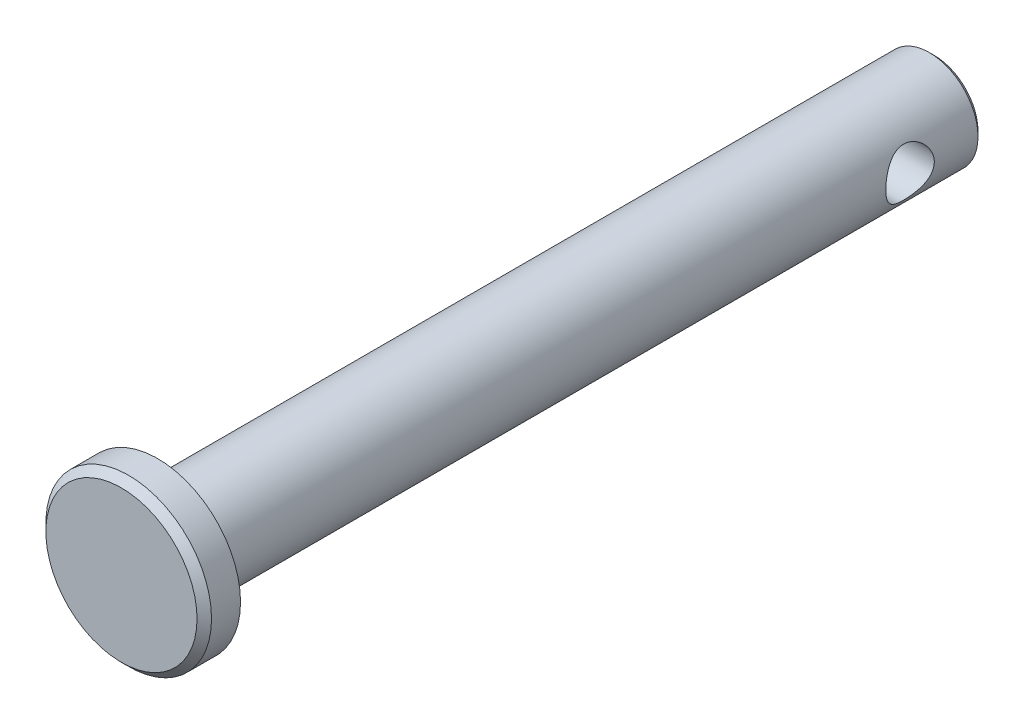
SolidWorks part; units mm, degrees
ref_plane "Front" through (0, 0, 0) normal (0, 0, 1) x (1, 0, 0)
ref_plane "Top" through (0, 0, 0) normal (0, 1, 0) x (1, 0, 0)
ref_plane "Right" through (0, 0, 0) normal (1, 0, 0) x (0, 0, -1)
sketch "Sketch1" plane through (0, 0, 0) normal (0, 0, 1) x (1, 0, 0)
  circle A0 centre (0, 0) radius 2.3812
  point P3 (0, 2.3812)
  point P4 (0, -2.3812)
  dimension "dia" = 4.7625
extrude "Extrude1" add sketch "Sketch1" along normal mid plane 38.1
sketch "Sketch2" plane through (0, 0, 19.05) normal (0, 0, 1) x (1, 0, 0)
  circle A0 centre (0, 0) radius 4.064
  dimension "head dia" = 8.128
extrude "Extrude2" add sketch "Sketch2" along normal blind 1.778
chamfer "Chamfer1" distance 0.3556 angle 45 1 edges at (4.064, 0, 20.828)
sketch "Sketch3" plane through (0, 0, 0) normal (1, 0, 0) x (0, 0, -1)
  line L0 (-19.05, -2.3812) -> (-19.05, 2.3812) construction
  circle A0 centre (15.4781, 0) radius 1.1906
  point P2 (14.2875, 0)
  dimension "hole dia" = 2.3813
  dimension "useable Lg" = 33.3375
extrude "Extrude3" cut sketch "Sketch3" against normal through all and the other way through all
chamfer "Chamfer2" distance 0.2381 angle 45 1 edges at (2.3812, 0, -19.05)
ref_plane "Plane1" through (0, 0, -15.4781) normal (0, 0, 1) x (1, 0, 0)
sketch "Sketch8" plane through (0, 0, 0) normal (1, 0, 0) x (0, 0, -1)
  line L0 (-20.828, 3.7084) -> (-20.828, -3.7084) construction
  line L1 (-20.4724, -4.064) -> (-19.05, -4.064) construction
  line L2 (19.05, -2.1431) -> (19.05, 2.1431) construction
  point P0 (-20.828, 4.064)
  point P1 (-19.05, 4.064)
  point P5 (19.05, 2.3812)
  point P8 (-20.828, -4.064)
  point P9 (19.05, -2.3812)
equation "\"D1@Chamfer1\" = \"head ht@Extrude2\" * .2"
equation "\"D1@Chamfer2\" = \"dia@Sketch1\" * .05"
